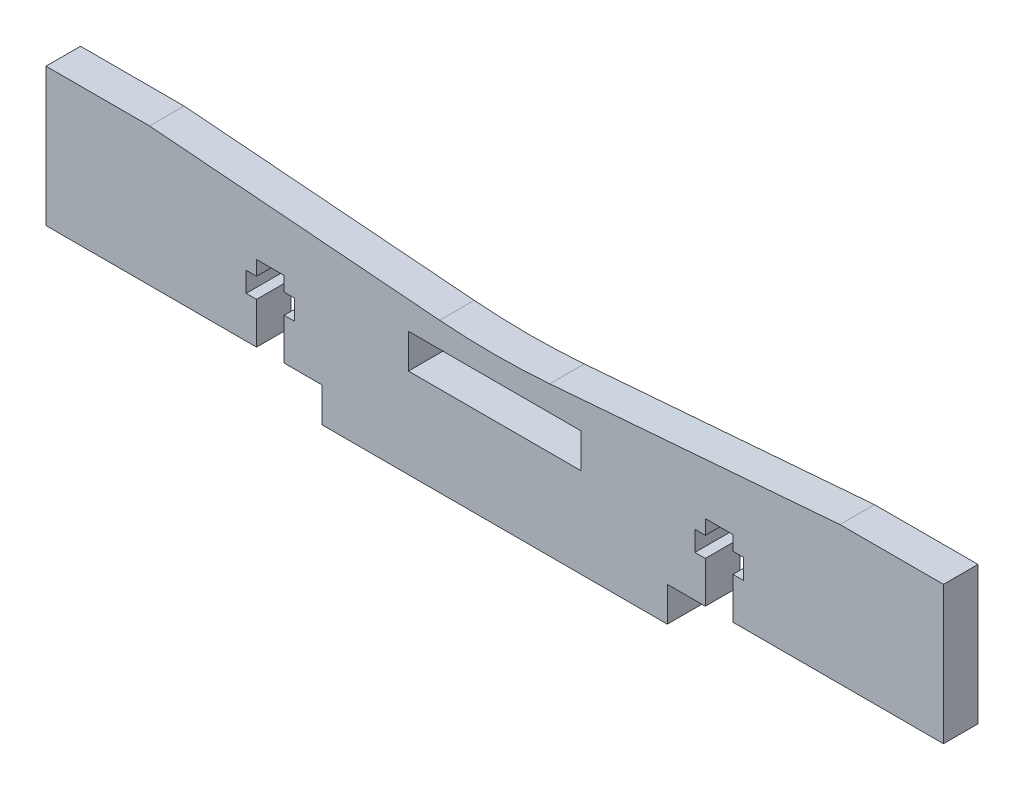
SolidWorks part; units mm, degrees
ref_plane "前视基准面" through (0, 0, 0) normal (0, 0, 1) x (1, 0, 0)
ref_plane "上视基准面" through (0, 0, 0) normal (0, 1, 0) x (1, 0, 0)
ref_plane "右视基准面" through (0, 0, 0) normal (1, 0, 0) x (0, 0, -1)
sketch "草图1" plane through (0, 0, 0) normal (0, 0, 1) x (1, 0, 0)
  line L0 (-34.5, 0) -> (-30.5, 0)
  line L1 (0, 0) -> (-130, 0)
  line L2 (0, 0) -> (0, 20)
  line L3 (0, 20) -> (-130, 20)
  line L4 (-130, 0) -> (-130, 20)
  line L5 (-34.5, 0) -> (-34.5, 11)
  line L6 (-34.5, 11) -> (-30.5, 11)
  line L7 (-30.5, 0) -> (-30.5, 11)
  line L8 (-36, 8.9) -> (-29, 8.9)
  line L9 (-36, 8.9) -> (-36, 6)
  line L10 (-36, 6) -> (-29, 6)
  line L11 (-29, 8.9) -> (-29, 6)
  line L12 (-99.5, 0) -> (-95.5, 0)
  line L13 (-90, 0) -> (-40, 0)
  line L14 (-90, 0) -> (-90, -5)
  line L15 (-90, -5) -> (-40, -5)
  line L16 (-40, 0) -> (-40, -5)
  line L17 (-99.5, 0) -> (-99.5, 11)
  line L18 (-99.5, 11) -> (-95.5, 11)
  line L19 (-95.5, 0) -> (-95.5, 11)
  line L20 (-101, 8.9) -> (-94, 8.9)
  line L21 (-101, 8.9) -> (-101, 6)
  line L22 (-101, 6) -> (-94, 6)
  line L23 (-94, 8.9) -> (-94, 6)
  line L24 (-115, 20) -> (-65, 16)
  line L25 (-65, 16) -> (-15, 20)
  line L26 (-65, -3.5874) -> (-65, 26.2173) construction
  line L28 (-77.5, 13) -> (-52.5, 13)
  line L29 (-77.5, 13) -> (-77.5, 8)
  line L30 (-77.5, 8) -> (-52.5, 8)
  line L31 (-52.5, 13) -> (-52.5, 8)
  point P13 (-36, 7.45)
  point P26 (-101, 7.45)
  point P32 (-65, 0)
  dimension "D1" = 130
  dimension "D2" = 4
  dimension "D3" = 7
  dimension "D4" = 11
  dimension "D5" = 2.9
  dimension "D6" = 1.5
  dimension "D7" = 0
  dimension "D8" = 4
  dimension "D9" = 7
  dimension "D10" = 11
  dimension "D11" = 2.9
  dimension "D12" = 1.5
  dimension "D13" = 0
  dimension "D14" = 5.5
  dimension "D15" = 5.5
  dimension "D16" = 50
  dimension "D17" = 5
  dimension "D18" = 40
  dimension "D19" = 6
  dimension "D20" = 6
  dimension "D21" = 20
  dimension "D22" = 15
  dimension "D23" = 15
  dimension "D24" = 4
  dimension "D25" = 5
  dimension "D26" = 25
  dimension "D27" = 12.5
  dimension "D28" = 3
extrude "凸台-拉伸1" add sketch "草图1" along normal blind 5
fillet "圆角1" radius 100 1 edges at (-65, 16, 2.5)
